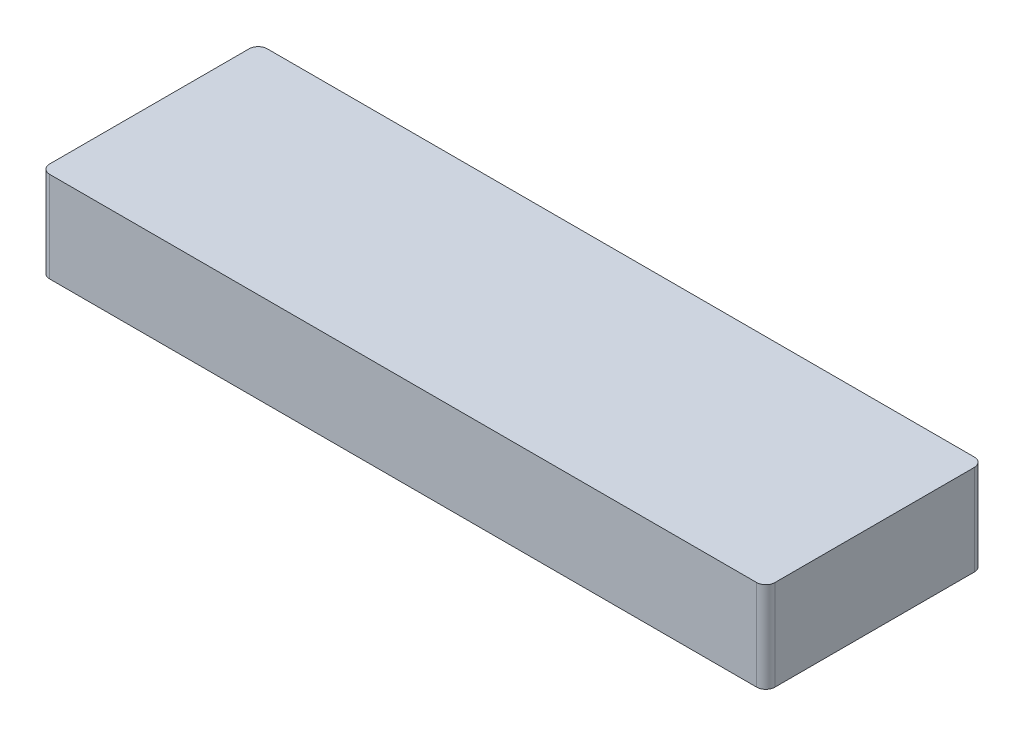
SolidWorks part; units mm, degrees
material "铜"
ref_plane "前视基准面" through (0, 0, 0) normal (0, 0, 1) x (1, 0, 0)
ref_plane "上视基准面" through (0, 0, 0) normal (0, 1, 0) x (1, 0, 0)
ref_plane "右视基准面" through (0, 0, 0) normal (1, 0, 0) x (0, 0, -1)
sketch "草图1" plane through (0, 0, 0) normal (0, 1, 0) x (1, 0, 0)
  line L1 (0, 0) -> (40, 0)
  line L2 (0, 0) -> (0, -12)
  line L3 (0, -12) -> (40, -12)
  line L4 (40, 0) -> (40, -12)
extrude "凸台-拉伸1" add sketch "草图1" along normal blind 5
fillet "圆角1" radius 0.5 4 edges at (0, 2.5, 0) (0, 2.5, 12) (40, 2.5, 0) (40, 2.5, 12)
